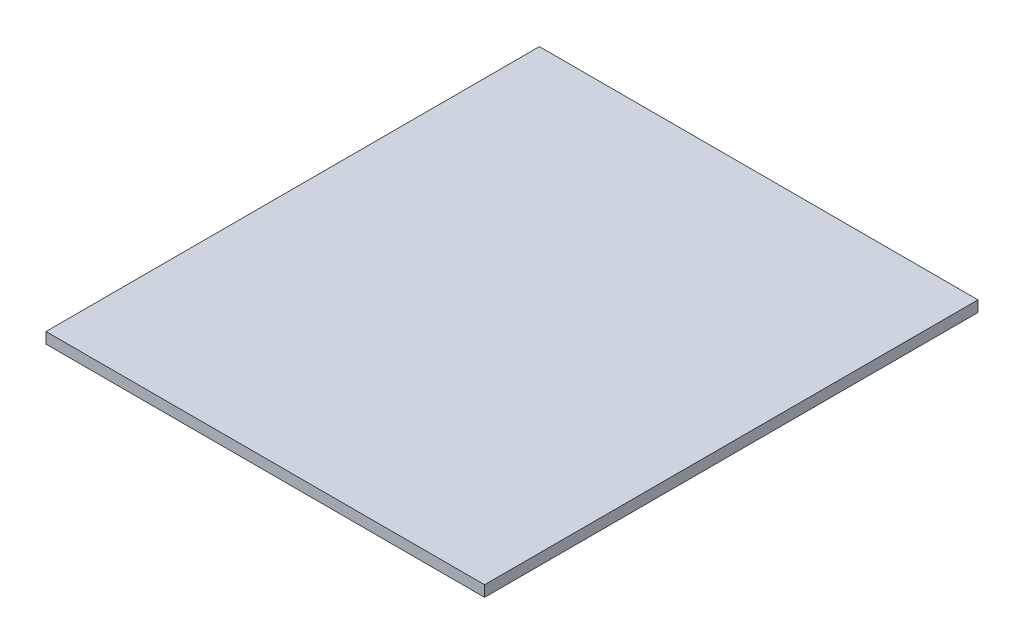
SolidWorks part; units mm, degrees
ref_plane "Front Plane" through (0, 0, 0) normal (0, 0, 1) x (1, 0, 0)
ref_plane "Top Plane" through (0, 0, 0) normal (0, 1, 0) x (1, 0, 0)
ref_plane "Right Plane" through (0, 0, 0) normal (1, 0, 0) x (0, 0, -1)
sketch "Sketch1" plane through (0, 0, 0) normal (0, 1, 0) x (1, 0, 0)
  line L1 (-200, -225) -> (200, -225)
  line L2 (-200, -225) -> (-200, 225)
  line L3 (-200, 225) -> (200, 225)
  line L4 (200, -225) -> (200, 225)
  line L5 (-200, -225) -> (200, 225) construction
  line L6 (-200, 225) -> (200, -225) construction
  point P0 (0, 0)
  dimension "D1" = 400
  dimension "D2" = 450
extrude "Boss-Extrude1" add sketch "Sketch1" along normal blind 10
